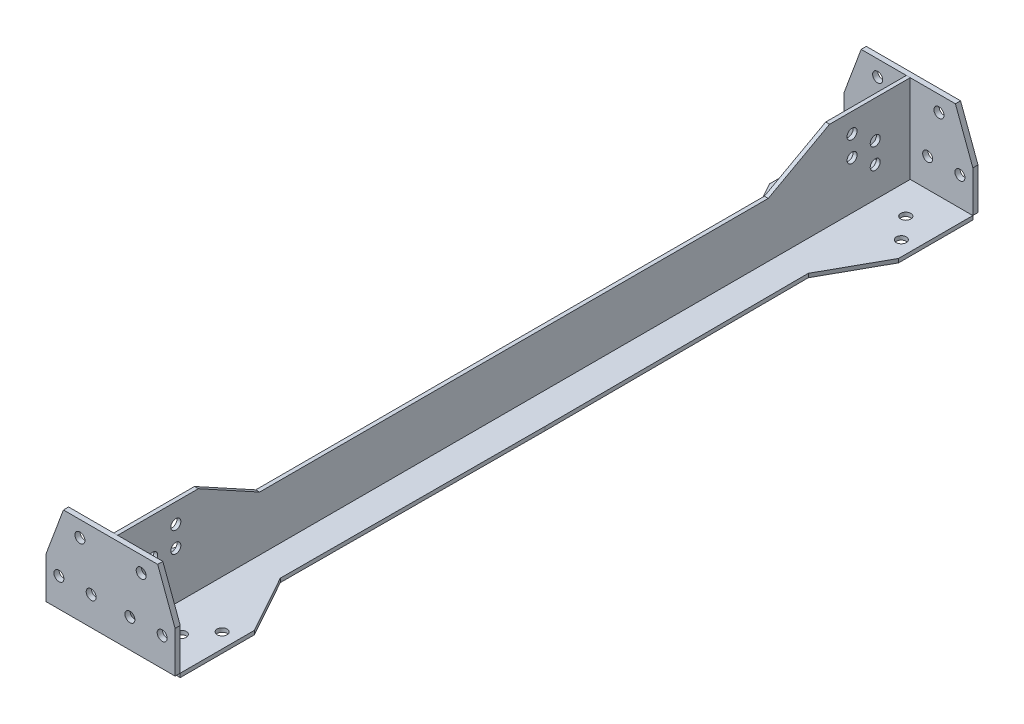
SolidWorks part; units mm, degrees
ref_plane "前视基准面" through (0, 0, 0) normal (0, 0, 1) x (1, 0, 0)
ref_plane "上视基准面" through (0, 0, 0) normal (0, 1, 0) x (1, 0, 0)
ref_plane "右视基准面" through (0, 0, 0) normal (1, 0, 0) x (0, 0, -1)
sketch "草图2" plane through (0, 0, 0) normal (0, 0, 1) x (1, 0, 0)
  line L0 (0, 0) -> (-87.1557, 0) construction
  line L2 (0, 0) -> (0, 66.6294) construction
  line L4 (-200, -6) -> (200, -6)
  line L5 (200, -6) -> (200, 6)
  line L6 (200, 6) -> (6, 6)
  line L7 (6, 6) -> (6, 279)
  line L8 (6, 279) -> (-6, 279)
  line L9 (-6, 279) -> (-6, 6)
  line L10 (-6, 6) -> (-200, 6)
  line L11 (-200, 6) -> (-200, -6)
  dimension "D1" = 400
  dimension "D2" = 285
  dimension "D3" = 12
  dimension "D4" = 12
extrude "拉伸1" add sketch "草图2" along normal blind 1228
sketch "草图4" plane through (0, 0, 1228) normal (0, 0, 1) x (1, 0, 0)
  line L0 (-200, 6) -> (-6, 6)
  line L1 (6, 279) -> (-6, 279)
  line L2 (-200, 6) -> (-200, 134)
  line L3 (-200, 134) -> (-146, 279)
  line L4 (-146, 279) -> (-6, 279)
  line L5 (6, 279) -> (-6, 279) construction
  line L6 (0, 0) -> (0, 380.8587) construction
  line L7 (-6, 6) -> (6, 6)
  line L9 (200, 134) -> (146, 279)
  line L10 (200, 6) -> (200, 134)
  line L11 (200, 6) -> (6, 6)
  line L12 (6, 279) -> (146, 279)
  point P18 (0, 279)
  dimension "D1" = 128
  dimension "D2" = 140
extrude "拉伸2" add sketch "草图4" along normal blind 16 separate body
sketch "草图5" plane through (0, 6, 0) normal (0, 1, 0) x (-1, 0, 0)
  line L0 (0, 0) -> (0, 1346.9983) construction
  line L1 (0, 1244) -> (-200, 995.2) construction
  line L3 (-200, 995.2) -> (0, 995.2) construction
  line L4 (-200, 0) -> (-200, 998)
  line L5 (200, 1228) -> (200, 0) construction
  line L6 (200, 998) -> (100, 818)
  line L7 (100, 818) -> (103, 0)
  line L8 (6, 0) -> (200, 0) construction
  line L9 (103, 0) -> (200, 0)
  line L10 (200, 0) -> (200, 998)
  line L11 (-103, 0) -> (-200, 0)
  line L12 (-100, 818) -> (-103, 0)
  line L13 (-200, 998) -> (-100, 818)
  line L14 (146, 1228) -> (200, 1228) construction
  line L15 (200, 1244) -> (-200, 1244) construction
  circle A0 centre (-97.7382, 1122.4137) radius 15.5
  circle A1 centre (-154.1257, 1052.2677) radius 15.5
  circle A2 centre (154.1257, 1052.2677) radius 15.5
  circle A3 centre (97.7382, 1122.4137) radius 15.5
  dimension "D5" = 31
  dimension "D1" = 200
  dimension "D2" = 156
  dimension "D3" = 248.8
  dimension "D4" = 90
  dimension "D6" = 230
  dimension "D7" = 100
  dimension "D8" = 180
extrude "拉伸3" cut sketch "草图5" against normal through all
sketch "草图6" plane through (6, 0, 0) normal (1, 0, 0) x (0, 0, -1)
  line L0 (0, 0) -> (-1361.6845, 0) construction
  line L1 (-1228, -6) -> (-1228, 5) construction
  line L2 (-1228, -6) -> (-1228, 6) construction
  line L3 (-1228, 5) -> (-1228, 70) construction
  line L4 (-1244, 70) -> (-979.2, 270) construction
  line L5 (-1455.6549, 70) -> (-769.4959, 70) construction
  line L6 (-1244, 6) -> (-1244, 134) construction
  line L7 (-979.2, 270) -> (-979.2, 70) construction
  line L8 (-1244, 6) -> (-1003.0142, 188.0135) construction
  line L11 (-1228, 279) -> (0, 279) construction
  line L12 (-978, 279) -> (-788, 175)
  line L13 (-788, 175) -> (0, 175)
  line L14 (0, 6) -> (0, 279) construction
  line L15 (0, 175) -> (0, 279)
  line L16 (0, 279) -> (-978, 279)
  circle A0 centre (-1119.5166, 164.0207) radius 15.5
  circle A1 centre (-1047.6993, 218.2634) radius 15.5
  circle A2 centre (-1119.5166, 100.0207) radius 15.5
  circle A3 centre (-1047.6993, 154.2634) radius 15.5
  dimension "D5" = 31
  dimension "D1" = 11
  dimension "D2" = 65
  dimension "D3" = 248.8
  dimension "D4" = 200
  dimension "D6" = 156
  dimension "D7" = 90
  dimension "D8" = 156
  dimension "D9" = 90
  dimension "D10" = 250
  dimension "D11" = 104
  dimension "D12" = 190
extrude "拉伸4" cut sketch "草图6" against normal through all
sketch "草图7" plane through (0, 0, 0) normal (0, 0, 1) x (1, 0, 0)
  line L1 (0, -42.1361) -> (0, 329.0525) construction
  line L3 (-236.8035, 0) -> (253.3013, 0) construction
  line L4 (6, 279) -> (-6, 279) construction
  line L5 (-200, -6) -> (200, -6) construction
  circle A0 centre (-95, 230) radius 15.5
  circle A1 centre (-60, 95) radius 15.5
  circle A2 centre (-160, 95) radius 15.5
  circle A3 centre (60, 95) radius 15.5
  circle A4 centre (160, 95) radius 15.5
  circle A5 centre (95, 230) radius 15.5
  dimension "D5" = 31
  dimension "D1" = 95
  dimension "D2" = 49
  dimension "D3" = 60
  dimension "D4" = 100
  dimension "D6" = 101
  dimension "D7" = 135
extrude "拉伸6" cut sketch "草图7" along normal through all
mirror "镜向1" about plane through (0, 0, 0) normal (0, 0, 1) of bodies 104
mirror "镜向2" about plane through (0, 0, 0) normal (0, 0, 1) of bodies 105
